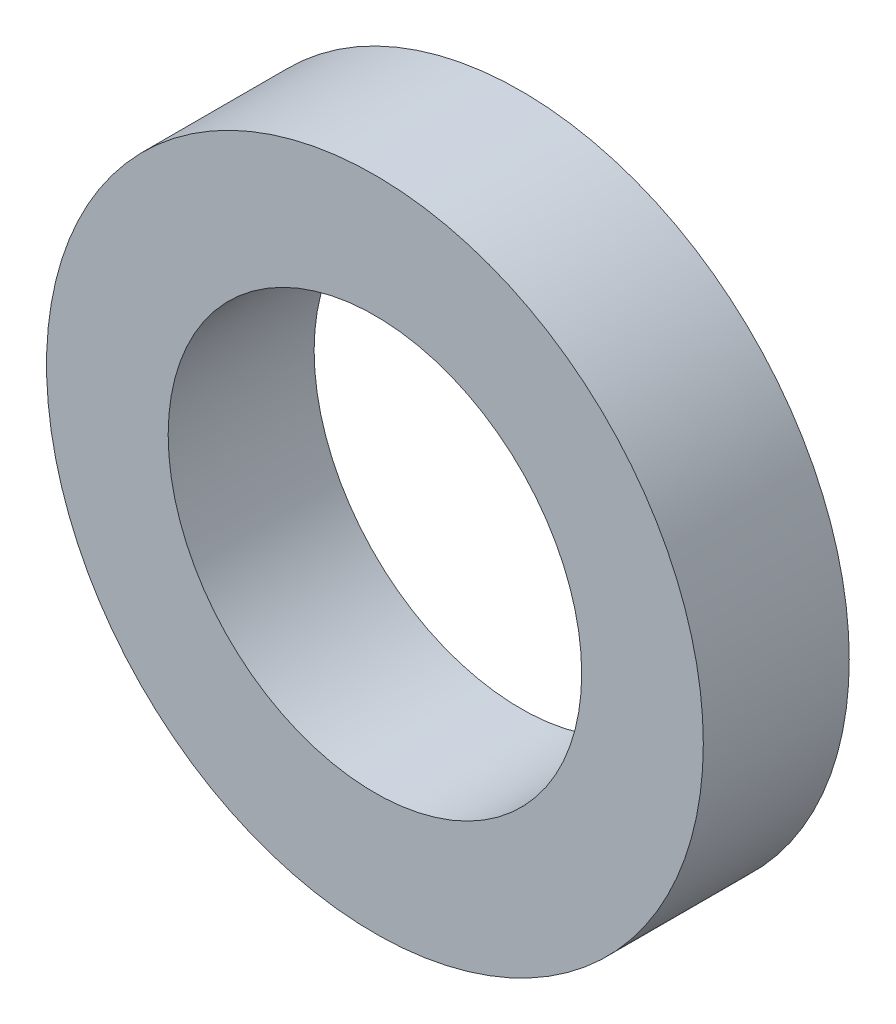
SolidWorks part; units mm, degrees
ref_plane "Piano frontale" through (0, 0, 0) normal (0, 0, 1) x (1, 0, 0)
ref_plane "Piano superiore" through (0, 0, 0) normal (0, 1, 0) x (1, 0, 0)
ref_plane "Piano destro" through (0, 0, 0) normal (1, 0, 0) x (0, 0, -1)
sketch "Schizzo1" plane through (0, 0, 0) normal (0, 0, 1) x (1, 0, 0)
  circle A0 centre (0, 0) radius 4.25
  circle A1 centre (0, 0) radius 6.75
  dimension "D1" = 8.5
  dimension "D2" = 13.5
extrude "Estrusione-Estrusione1" add sketch "Schizzo1" along normal blind 3
